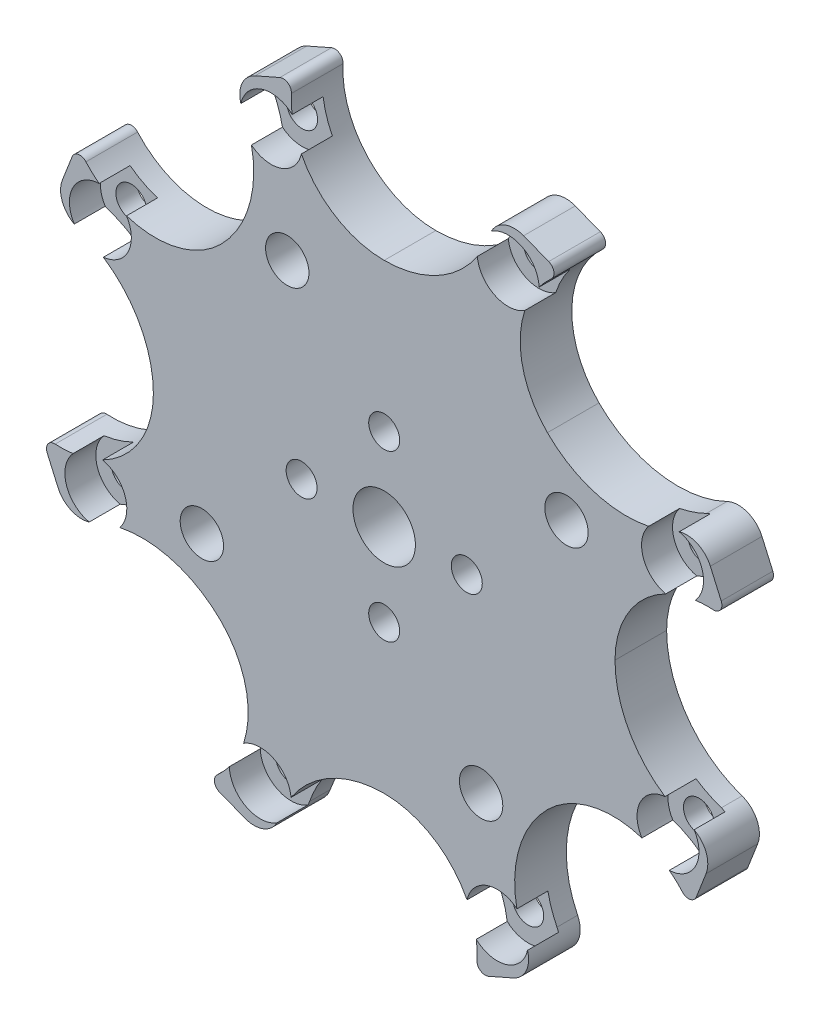
SolidWorks part; units mm, degrees
ref_plane "前视基准面" through (0, 0, 0) normal (0, 0, 1) x (1, 0, 0)
ref_plane "上视基准面" through (0, 0, 0) normal (0, 1, 0) x (1, 0, 0)
ref_plane "右视基准面" through (0, 0, 0) normal (1, 0, 0) x (0, 0, -1)
sketch "草图1" plane through (0, 0, 0) normal (0, 0, 1) x (1, 0, 0)
  line L0 (0, 31.3575) -> (0, 0) construction
  line L1 (0, 0) -> (22.1731, 22.1731) construction
  line L4 (0, 31.3575) -> (22.1731, 22.1731) construction
  line L6 (11.6409, 26.5357) -> (12.5976, 28.8454) construction
  line L7 (22.2808, 22.9688) -> (16.1797, 28.8872) construction
  line L8 (22.2808, 22.9688) -> (28.5472, 29.4288) construction
  line L9 (15.9368, 30.2296) -> (13.5034, 31.1755)
  line L10 (32.6446, 10.1066) -> (31.5928, 12.4961)
  line L11 (30.2296, -15.9368) -> (31.1755, -13.5034)
  line L12 (10.1066, -32.6446) -> (12.4961, -31.5928)
  line L13 (-15.9368, -30.2296) -> (-13.5034, -31.1755)
  line L14 (-32.6446, -10.1066) -> (-31.5928, -12.4961)
  line L15 (-30.2296, 15.9368) -> (-31.1755, 13.5034)
  line L16 (-10.1066, 32.6446) -> (-12.4961, 31.5928)
  circle A0 centre (0, 0) radius 31.3575 construction
  arc A9 (16.1797, 28.8872) -> (15.8091, 15.8091) centre (22.1731, 22.1731) ccw
  circle A13 centre (0, 0) radius 41 construction
  arc A16 (16.1797, 28.8872) -> (15.9368, 30.2296) centre (15.6469, 29.484) ccw
  arc A17 (13.5034, 31.1755) -> (10.2336, 29.6588) centre (12.5976, 28.8454) ccw
  arc A18 (0, 22.3575) -> (10.2336, 29.6588) centre (0, 33.18) ccw
  arc A19 (31.8671, 8.9856) -> (22.3575, 0) centre (31.3575, 0) ccw
  arc A20 (31.8671, 8.9856) -> (32.6446, 10.1066) centre (31.9124, 9.7843) ccw
  arc A21 (31.5928, 12.4961) -> (28.2082, 13.7357) centre (29.3046, 11.4889) ccw
  arc A22 (15.8091, 15.8091) -> (28.2082, 13.7357) centre (23.4618, 23.4618) ccw
  arc A24 (28.8872, -16.1797) -> (15.8091, -15.8091) centre (22.1731, -22.1731) ccw
  arc A25 (28.8872, -16.1797) -> (30.2296, -15.9368) centre (29.484, -15.6469) ccw
  arc A26 (31.1755, -13.5034) -> (29.6588, -10.2336) centre (28.8454, -12.5976) ccw
  arc A27 (22.3575, 0) -> (29.6588, -10.2336) centre (33.18, 0) ccw
  arc A29 (8.9856, -31.8671) -> (0, -22.3575) centre (0, -31.3575) ccw
  arc A30 (8.9856, -31.8671) -> (10.1066, -32.6446) centre (9.7843, -31.9124) ccw
  arc A31 (12.4961, -31.5928) -> (13.7357, -28.2082) centre (11.4889, -29.3046) ccw
  arc A32 (15.8091, -15.8091) -> (13.7357, -28.2082) centre (23.4618, -23.4618) ccw
  arc A34 (-16.1797, -28.8872) -> (-15.8091, -15.8091) centre (-22.1731, -22.1731) ccw
  arc A35 (-16.1797, -28.8872) -> (-15.9368, -30.2296) centre (-15.6469, -29.484) ccw
  arc A36 (-13.5034, -31.1755) -> (-10.2336, -29.6588) centre (-12.5976, -28.8454) ccw
  arc A37 (0, -22.3575) -> (-10.2336, -29.6588) centre (0, -33.18) ccw
  arc A39 (-31.8671, -8.9856) -> (-22.3575, 0) centre (-31.3575, 0) ccw
  arc A40 (-31.8671, -8.9856) -> (-32.6446, -10.1066) centre (-31.9124, -9.7843) ccw
  arc A41 (-31.5928, -12.4961) -> (-28.2082, -13.7357) centre (-29.3046, -11.4889) ccw
  arc A42 (-15.8091, -15.8091) -> (-28.2082, -13.7357) centre (-23.4618, -23.4618) ccw
  arc A44 (-28.8872, 16.1797) -> (-15.8091, 15.8091) centre (-22.1731, 22.1731) ccw
  arc A45 (-28.8872, 16.1797) -> (-30.2296, 15.9368) centre (-29.484, 15.6469) ccw
  arc A46 (-31.1755, 13.5034) -> (-29.6588, 10.2336) centre (-28.8454, 12.5976) ccw
  arc A47 (-22.3575, 0) -> (-29.6588, 10.2336) centre (-33.18, 0) ccw
  arc A49 (-8.9856, 31.8671) -> (0, 22.3575) centre (0, 31.3575) ccw
  arc A50 (-8.9856, 31.8671) -> (-10.1066, 32.6446) centre (-9.7843, 31.9124) ccw
  arc A51 (-12.4961, 31.5928) -> (-13.7357, 28.2082) centre (-11.4889, 29.3046) ccw
  arc A52 (-15.8091, 15.8091) -> (-13.7357, 28.2082) centre (-23.4618, 23.4618) ccw
  circle A54 centre (0, 0) radius 3.025
  circle A55 centre (0, 0) radius 8 construction
  circle A56 centre (-8, 0) radius 1.5
  circle A57 centre (0, 8) radius 1.5
  circle A58 centre (8, 0) radius 1.5
  circle A59 centre (0, -8) radius 1.5
  point P98 (0, 0)
  point P102 (0, 0)
  dimension "D1" = 9
  dimension "D3" = 45
  dimension "D5" = 9
  dimension "D8" = 82
  dimension "D9" = 9
  dimension "D10" = 2.5
  dimension "D11" = 0.8
  dimension "D13" = 6.05
  dimension "D14" = 16
  dimension "D15" = 3
  dimension "D2" = 24
  dimension "D6" = 11.4
  dimension "D7" = 2.5
  dimension "D17" = 8.5
  dimension "D12" = 8
  dimension "D16" = 4
extrude "凸台-拉伸1" add sketch "草图1" along normal blind 5
sketch "草图2" plane through (0, 0, 5) normal (0, 0, 1) x (1, 0, 0)
  line L0 (0, 0) -> (-22.3575, 0) construction
  line L1 (-9.3894, 17.659) -> (0, 0) construction
  circle A0 centre (0, 0) radius 20 construction
  circle A1 centre (-17.659, -9.3894) radius 2.1
  arc A2 (-22.3575, 0) -> (-29.6588, 10.2336) centre (-33.18, 0) ccw construction
  circle A3 centre (-9.3894, 17.659) radius 2.1
  circle A4 centre (17.659, 9.3894) radius 2.1
  circle A5 centre (9.3894, -17.659) radius 2.1
  point P19 (0, 0)
  dimension "D1" = 40
  dimension "D2" = 4.2
  dimension "D4" = 62
  dimension "D3" = 4
extrude "切除-拉伸1" cut sketch "草图2" against normal blind 10
sketch "草图3" plane through (0, 0, 5) normal (0, 0, 1) x (1, 0, 0)
  line L0 (0, 0) -> (-11.4889, 29.3046) construction
  line L1 (0, 0) -> (-22.3575, 0) construction
  arc A2 (-12.4961, 31.5928) -> (-13.7357, 28.2082) centre (-11.4889, 29.3046) ccw construction
  arc A3 (-12.4961, 31.5928) -> (-13.7357, 28.2082) centre (-11.4889, 29.3046) ccw construction
  circle A4 centre (0, 0) radius 30 construction
  circle A5 centre (-10.9501, 27.9302) radius 1.5
  circle A6 centre (12.0067, 27.4925) radius 1.5
  circle A7 centre (27.9302, 10.9501) radius 1.5
  circle A8 centre (27.4925, -12.0067) radius 1.5
  circle A9 centre (10.9501, -27.9302) radius 1.5
  circle A10 centre (-12.0067, -27.4925) radius 1.5
  circle A11 centre (-27.9302, -10.9501) radius 1.5
  circle A12 centre (-27.4925, 12.0067) radius 1.5
  point P27 (0, 0)
  dimension "D1" = 60
  dimension "D2" = 3
  dimension "D3" = 8
extrude "切除-拉伸3" cut sketch "草图3" against normal blind 10
sketch "草图4" plane through (0, 0, 0) normal (0, 0, -1) x (-1, 0, 0)
  line L0 (-17.659, 9.3894) -> (-23.4618, 23.4618) construction
  line L1 (-15.463, 7.6989) -> (-15.0969, 10.4459)
  line L2 (-15.0969, 10.4459) -> (-17.2929, 12.1364)
  line L3 (-17.2929, 12.1364) -> (-19.8549, 11.08)
  line L4 (-19.8549, 11.08) -> (-20.221, 8.333)
  line L5 (-20.221, 8.333) -> (-18.025, 6.6424)
  line L6 (-18.025, 6.6424) -> (-15.463, 7.6989)
  circle A0 centre (-17.659, 9.3894) radius 2.4 construction
  circle A1 centre (-19.8549, 11.08) radius 0.75
  circle A2 centre (-17.2929, 12.1364) radius 0.75
  circle A3 centre (-15.0969, 10.4459) radius 0.75
  circle A4 centre (-15.463, 7.6989) radius 0.75
  circle A5 centre (-18.025, 6.6424) radius 0.75
  circle A6 centre (-20.221, 8.333) radius 0.75
  dimension "D3" = 1.5
  dimension "D1" = 4.8
  dimension "D4" = 6
extrude "切除-拉伸4" cut sketch "草图4" against normal blind 1 contours A6 L5 A5 L6 A4 L1 A3 L2 A2 L3 A1 L4 | L2 A2 L3 | L3 A2 L2 | L1 A3 L2 | L2 A3 L1 | L3 A1 L4 | L4 A1 L3 | L5 A6 L4 | L4 A6 L5 | L5 A5 L6 | L6 A5 L5 | L6 A4 L1 | L1 A4 L6
pattern_circular "阵列(圆周)1" count 4 over 360 about axis through (0, 0, 0) along (0, 0, 1) of "切除-拉伸4"
sketch "草图5" plane through (0, 0, 5) normal (0, 0, 1) x (1, 0, 0)
  circle A0 centre (12.0067, 27.4925) radius 3
  circle A1 centre (27.9302, 10.9501) radius 3
  circle A2 centre (27.4925, -12.0067) radius 3
  circle A3 centre (10.9501, -27.9302) radius 3
  circle A4 centre (-12.0067, -27.4925) radius 3
  circle A5 centre (-27.9302, -10.9501) radius 3
  circle A6 centre (-27.4925, 12.0067) radius 3
  circle A7 centre (-10.9501, 27.9302) radius 3
  point P3 (0, 0)
  point P5 (0, 0)
  point P20 (0, 0)
  dimension "D1" = 6
  dimension "D2" = 8
extrude "切除-拉伸5" cut sketch "草图5" against normal blind 3
